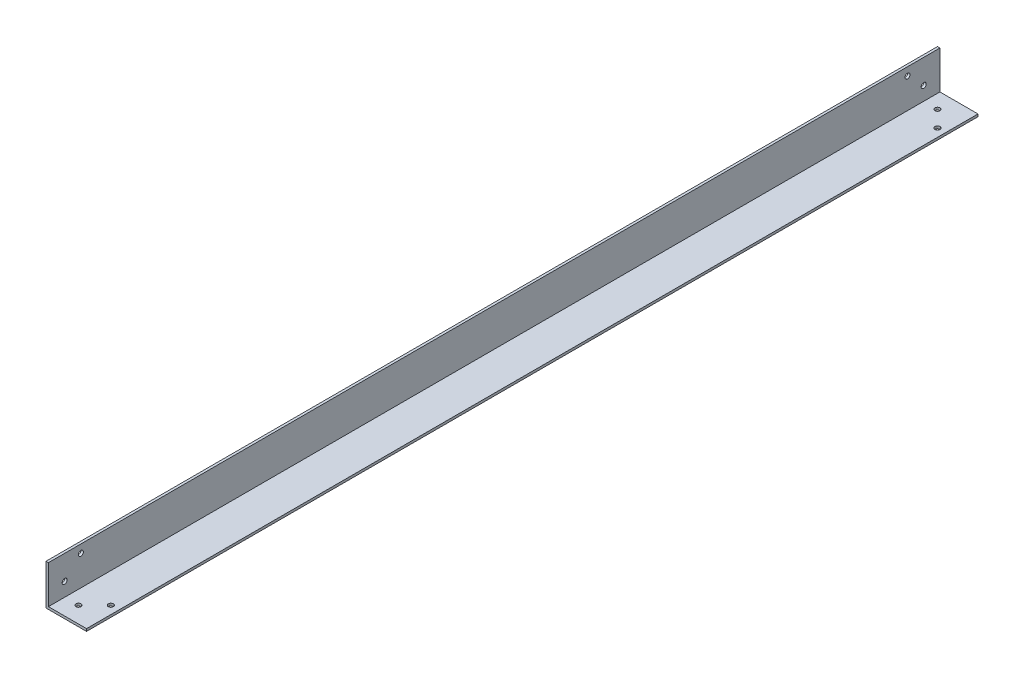
SolidWorks part; units mm, degrees
ref_plane "Front Plane" through (0, 0, 0) normal (0, 0, 1) x (1, 0, 0)
ref_plane "Top Plane" through (0, 0, 0) normal (0, 1, 0) x (1, 0, 0)
ref_plane "Right Plane" through (0, 0, 0) normal (1, 0, 0) x (0, 0, -1)
sketch "Sketch1" plane through (0, 0, 0) normal (0, 0, 1) x (1, 0, 0)
  line L0 (0, 0) -> (0, 25)
  line L1 (0, 25) -> (1.5, 25)
  line L2 (1.5, 25) -> (1.5, 1.5)
  line L3 (1.5, 1.5) -> (25, 1.5)
  line L4 (25, 1.5) -> (25, 0)
  line L5 (25, 0) -> (0, 0)
  dimension "D1" = 1.5
  dimension "D2" = 25
extrude "Boss-Extrude1" add sketch "Sketch1" along normal blind 550
sketch "Sketch2" plane through (0, 0, 0) normal (-1, 0, 0) x (0, 0, 1)
  line L0 (10, 10) -> (540, 10) construction
  line L1 (20, 20) -> (530, 20) construction
  line L2 (550, 25) -> (0, 25) construction
  line L3 (0, 25) -> (0, 0) construction
  line L4 (550, 25) -> (550, 0) construction
  circle A0 centre (10, 10) radius 1.55
  circle A1 centre (20, 20) radius 1.55
  circle A2 centre (530, 20) radius 1.55
  circle A3 centre (540, 10) radius 1.55
  dimension "D1" = 3.1
  dimension "D2" = 5
  dimension "D3" = 15
  dimension "D4" = 20
  dimension "D5" = 10
  dimension "D6" = 10
  dimension "D7" = 20
extrude "Cut-Extrude1" cut sketch "Sketch2" against normal blind 10
sketch "Sketch3" plane through (0, 0, 0) normal (0, -1, 0) x (1, 0, 0)
  line L0 (20, 530) -> (20, 20) construction
  line L1 (25, 550) -> (25, 0) construction
  line L2 (10, 10) -> (10, 540) construction
  line L3 (0, 0) -> (25, 0) construction
  line L4 (0, 550) -> (25, 550) construction
  circle A0 centre (10, 540) radius 1.55
  circle A1 centre (20, 530) radius 1.55
  circle A2 centre (20, 20) radius 1.55
  circle A3 centre (10, 10) radius 1.55
  dimension "D1" = 3.1
  dimension "D2" = 5
  dimension "D3" = 15
  dimension "D4" = 10
  dimension "D5" = 20
  dimension "D6" = 10
  dimension "D7" = 20
extrude "Cut-Extrude2" cut sketch "Sketch3" against normal blind 10
